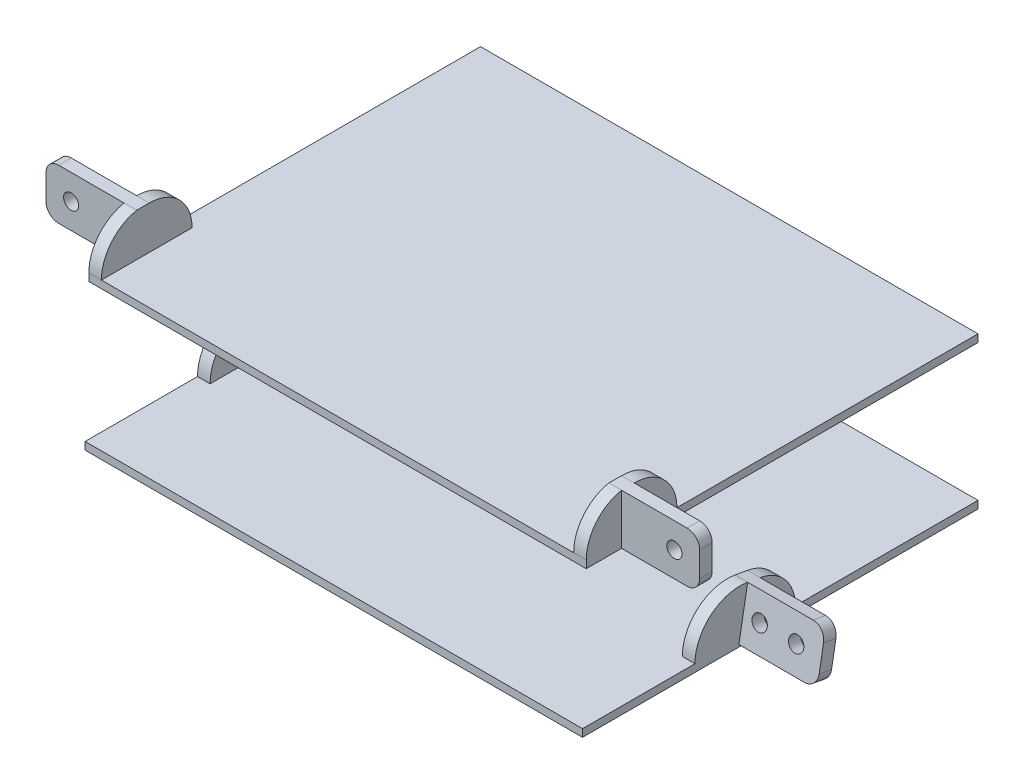
SolidWorks part; units mm, degrees
ref_plane "Front Plane" through (0, 0, 0) normal (0, 0, 1) x (1, 0, 0)
ref_plane "Top Plane" through (0, 0, 0) normal (0, 1, 0) x (1, 0, 0)
ref_plane "Right Plane" through (0, 0, 0) normal (1, 0, 0) x (0, 0, -1)
sketch "Sketch3" plane through (0, 0, 0) normal (0, 0, 1) x (1, 0, 0)
  line L0 (-76.2993, 0) -> (18.6887, 0)
ref_plane "Lower tab plane" through (0, 0, 0) normal (0, 0.1736, 0.9848) x (1, 0, 0)
sketch "Sketch1" plane through (0, 0, 0) normal (0, 0.1736, 0.9848) x (1, 0, 0)
  line L1 (-124.75, 10) -> (-93.75, 10)
  line L2 (-129.75, 5) -> (-129.75, -5)
  line L3 (-124.75, -10) -> (-93.75, -10)
  line L4 (-93.75, 10) -> (-93.75, -10)
  circle A0 centre (-119.75, 0) radius 3
  circle A1 centre (-105.25, 0) radius 3
  arc A2 (-129.75, -5) -> (-124.75, -10) centre (-124.75, -5) ccw
  arc A3 (-124.75, 10) -> (-129.75, 5) centre (-124.75, 5) ccw
  point P4 (-93.75, 0)
  point P18 (-129.75, 10)
  dimension "D4" = 6
  dimension "D5" = 6
  dimension "D8" = 5
  dimension "D1" = 36
  dimension "D2" = 20
  dimension "D3" = 119.75
  dimension "D6" = 14.5
  dimension "D7" = 10
extrude "Lower left tab" add sketch "Sketch1" along normal blind 5
sketch "Sketch2" plane through (-93.75, 0, 0) normal (1, 0, 0) x (0, 0, -1)
  line L1 (-68.7365, -6.8481) -> (88.2635, -6.8481)
  line L2 (-68.7365, -6.8481) -> (-68.7365, -9.8481)
  line L3 (-68.7365, -9.8481) -> (88.2635, -9.8481)
  line L4 (88.2635, -6.8481) -> (88.2635, -9.8481)
  dimension "D1" = 3
  dimension "D2" = 90
  dimension "D3" = 67
extrude "Bottom plate extrude" add sketch "Sketch2" along normal blind 93.75 and the other way blind 5
sketch "Sketch4" plane through (-93.75, 0, 0) normal (1, 0, 0) x (0, 0, -1)
  line L0 (88.2635, -6.8481) -> (-68.7365, -6.8481) construction
  line L1 (15.7462, -6.8481) -> (-1.2075, -6.8481)
  line L2 (-6.2846, -6.8481) -> (-3.1876, 10.7163) construction
  line L3 (-1.2075, -6.8481) -> (1.7365, 9.8481) construction
  line L4 (-6.2846, -6.8481) -> (-3.1876, 10.7163)
  line L5 (-1.2075, -6.8481) -> (1.7365, 9.8481)
  line L6 (-6.2846, -6.8481) -> (-24.12, -6.8481)
  line L7 (-3.1876, 10.7163) -> (1.7365, 9.8481) construction
  arc A0 (1.7365, 9.8481) -> (15.7462, -6.8481) centre (-1.2075, -6.8481) cw
  arc A1 (-3.1876, 10.7163) -> (-24.12, -6.8481) centre (-6.2846, -6.8481) ccw
extrude "Bottom tab support extrude" add sketch "Sketch4" against normal blind 5
ref_plane "Plane2" through (0, 0, -1.7365) normal (0, 0, 1) x (1, 0, 0)
ref_plane "Top tab plane" through (0, 0, 48.2635) normal (0, 0, 1) x (1, 0, 0)
sketch "Sketch5" plane through (0, 0, 48.2635) normal (0, 0, 1) x (1, 0, 0)
  line L0 (-129.75, 5.7923) -> (-129.75, -4.0558) construction
  line L1 (-124.75, 67.4019) -> (-93.75, 67.4019)
  line L2 (-129.75, 62.4019) -> (-129.75, 52.4019)
  line L3 (-124.75, 47.4019) -> (-93.75, 47.4019)
  line L4 (-93.75, 67.4019) -> (-93.75, 47.4019)
  line L5 (-93.75, -6.8481) -> (-93.75, 10.9873) construction
  arc A0 (-129.75, 52.4019) -> (-124.75, 47.4019) centre (-124.75, 52.4019) ccw
  arc A1 (-124.75, 67.4019) -> (-129.75, 62.4019) centre (-124.75, 62.4019) ccw
  circle A2 centre (-119.75, 57.4019) radius 3
  ellipse E0 centre (-119.75, 0.8682) end of major axis (-116.75, 0.8682) minor radius 2.9544 construction
  ellipse E1 centre (-119.75, 0.8682) end of major axis (-116.75, 0.8682) minor radius 2.9544 construction
  point P28 (-93.75, 57.4019)
  dimension "D2" = 5
  dimension "D3" = 6
  dimension "D1" = 20
  dimension "D4" = 67.25
extrude "Top tab extrude" add sketch "Sketch5" along normal blind 5 separate body
sketch "Sketch6" plane through (-93.75, 0, 0) normal (1, 0, 0) x (0, 0, -1)
  line L0 (-53.2635, 47.4019) -> (-48.2635, 47.4019) construction
  line L1 (-67.2635, 47.4019) -> (88.2635, 47.4019)
  line L2 (-67.2635, 47.4019) -> (-67.2635, 50.4019)
  line L3 (-67.2635, 50.4019) -> (88.2635, 50.4019)
  line L4 (88.2635, 47.4019) -> (88.2635, 50.4019)
  line L5 (-48.2635, 47.4019) -> (-48.2635, 67.4019) construction
  line L6 (88.2635, -9.8481) -> (88.2635, -6.8481) construction
  dimension "D1" = 3
  dimension "D2" = 19
extrude "Top plate extrude" add sketch "Sketch6" against normal blind 5 and the other way up to surface (93.75 mm away) other way up to face at (0, -8.3481, -9.7635)
sketch "Sketch7" plane through (-93.75, 0, 0) normal (1, 0, 0) x (0, 0, -1)
  line L0 (-48.2635, 50.4019) -> (-48.2635, 67.4019) construction
  line L1 (88.2635, 50.4019) -> (-67.2635, 50.4019) construction
  line L2 (-53.2635, 50.4019) -> (-53.2635, 67.4019) construction
  line L3 (-48.2635, 50.4019) -> (-48.2635, 67.4019)
  line L4 (-31.2635, 50.4019) -> (-48.2635, 50.4019)
  line L5 (-53.2635, 50.4019) -> (-53.2635, 67.4019)
  line L6 (-53.2635, 50.4019) -> (-67.2635, 50.4019)
  line L7 (-67.2635, 50.4019) -> (-67.2635, 47.4019) construction
  arc A0 (-67.2635, 50.4019) -> (-53.2635, 67.4019) centre (-49.9421, 50.4019) cw
  arc A1 (-48.2635, 67.4019) -> (-31.2635, 50.4019) centre (-48.2635, 50.4019) cw
extrude "Top tab support extrude" add sketch "Sketch7" against normal blind 5
mirror "Mirror" about plane through (0, 0, 0) normal (1, 0, 0) of "Top tab extrude", "Top plate extrude", "Top tab support extrude", "Lower left tab", "Bottom plate extrude", "Bottom tab support extrude"
ref_plane "Split plane" through (0, 30, 0) normal (0, 1, 0) x (1, 0, 0)
split "Split1" trim tools "Split plane" bodies to split 109 110 resulting bodies 107 108
